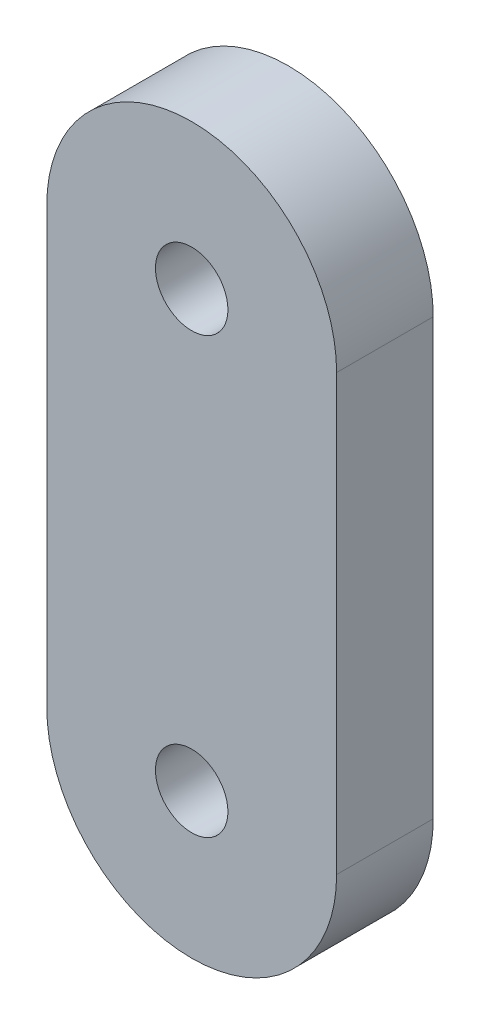
SolidWorks part; units mm, degrees
ref_plane "前视基准面" through (0, 0, 0) normal (0, 0, 1) x (1, 0, 0)
ref_plane "上视基准面" through (0, 0, 0) normal (0, 1, 0) x (1, 0, 0)
ref_plane "右视基准面" through (0, 0, 0) normal (1, 0, 0) x (0, 0, -1)
ref_plane "基准面4" through (0, 0, 8) normal (0, 0, 1) x (1, 0, 0)
sketch "草图1" plane through (0, 0, 8) normal (0, 0, 1) x (1, 0, 0)
  line L0 (12, -36) -> (12, 0)
  line L1 (-12, 0) -> (-12, -36)
  circle A0 centre (0, -36) radius 3
  circle A1 centre (0, 0) radius 3
  arc A5 (12, 0) -> (-12, 0) centre (0, 0) ccw
  arc A6 (-12, -36) -> (12, -36) centre (0, -36) ccw
  dimension "D1" = 36
  dimension "D3" = 36
  dimension "D5" = 12
extrude "凸台-拉伸1" add sketch "草图1" against normal blind 8
